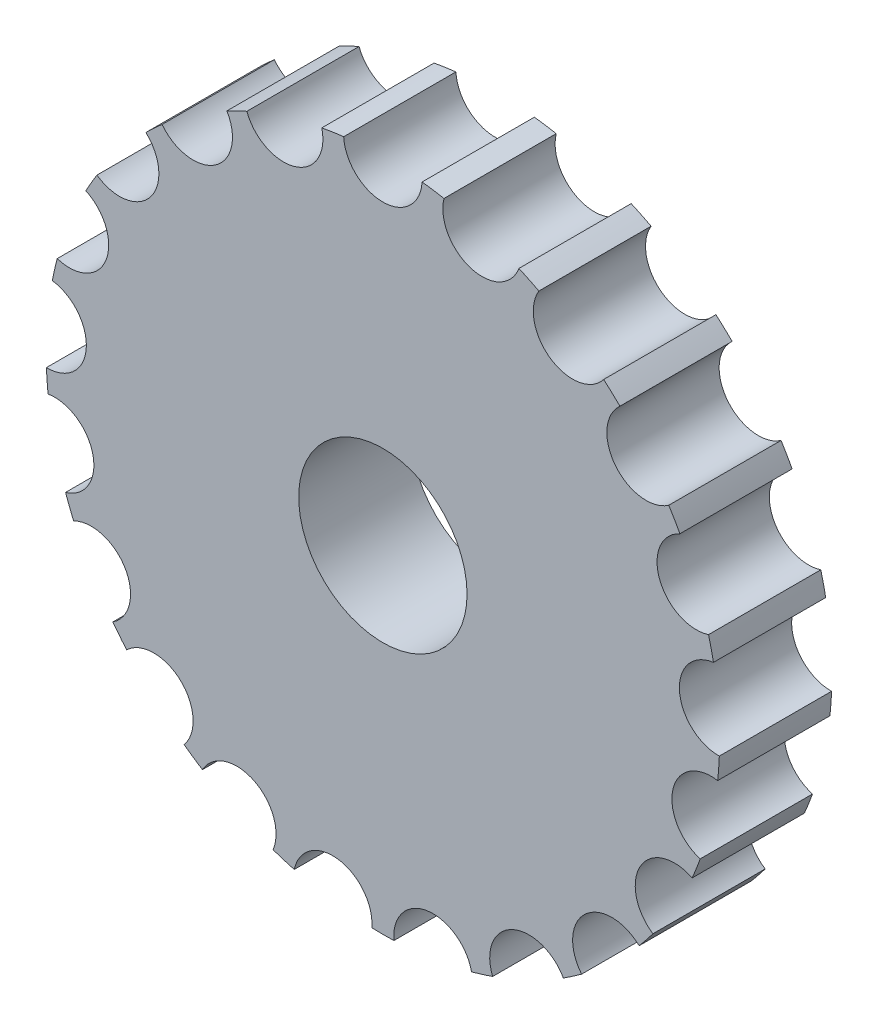
SolidWorks part; units mm, degrees
ref_plane "Front Plane" through (0, 0, 0) normal (0, 0, 1) x (1, 0, 0)
ref_plane "Top Plane" through (0, 0, 0) normal (0, 1, 0) x (1, 0, 0)
ref_plane "Right Plane" through (0, 0, 0) normal (1, 0, 0) x (0, 0, -1)
sketch "Sketch1" plane through (0, 0, 0) normal (0, 0, 1) x (1, 0, 0)
  circle A0 centre (0, 0) radius 38.1
  circle A1 centre (0, 0) radius 9.525
  dimension "D1" = 76.2
  dimension "D2" = 19.05
extrude "Boss-Extrude1" add sketch "Sketch1" along normal blind 12.7
sketch "Sketch2" plane through (0, 0, 12.7) normal (0, 0, 1) x (1, 0, 0)
  line L0 (0, 38.1) -> (0, 0) construction
  circle A0 centre (0, 38.1) radius 4.445
  circle A1 centre (0, 0) radius 38.1 construction
  dimension "D1" = 8.89
extrude "Cut-Extrude1" cut sketch "Sketch2" against normal through all
pattern_circular "CirPattern1" count 21 over 360 about axis through (0, 0, 0) along (0, 0, 1) of "Cut-Extrude1"
